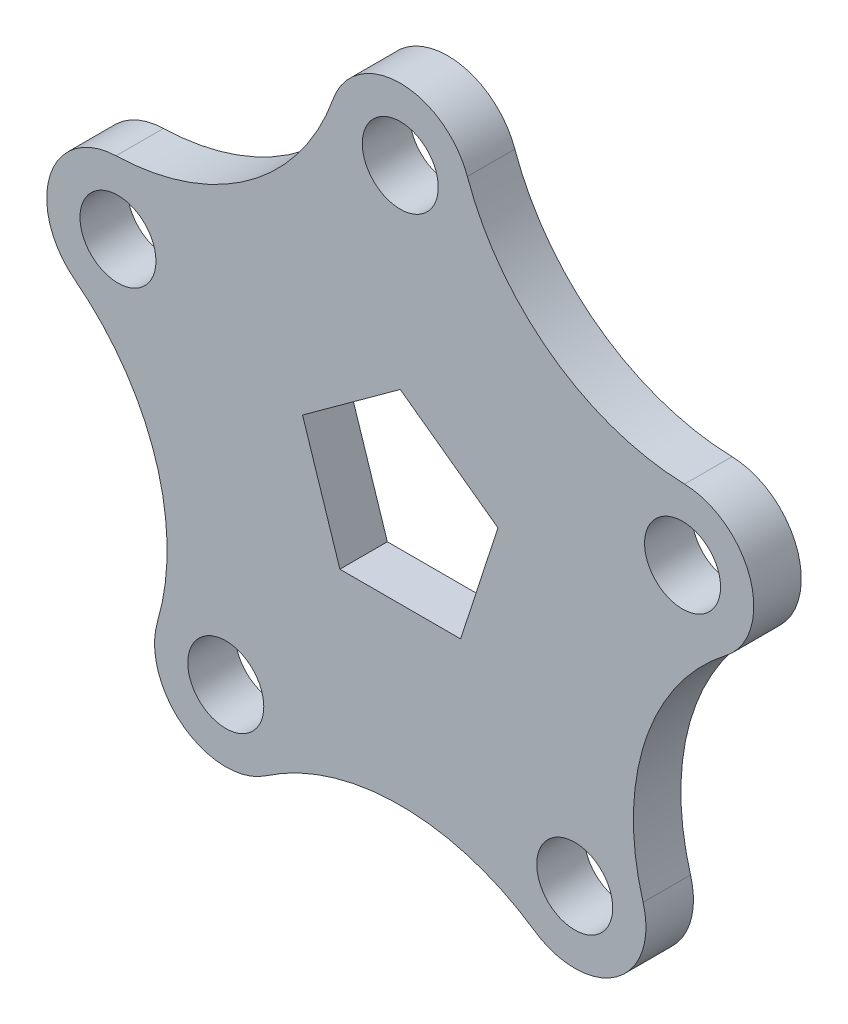
SolidWorks part; units mm, degrees
ref_plane "Płaszczyzna przednia" through (0, 0, 0) normal (0, 0, 1) x (1, 0, 0)
ref_plane "Płaszczyzna górna" through (0, 0, 0) normal (0, 1, 0) x (1, 0, 0)
ref_plane "Płaszczyzna prawa" through (0, 0, 0) normal (1, 0, 0) x (0, 0, -1)
sketch "Szkic1" plane through (0, 0, 0) normal (0, 0, 1) x (1, 0, 0)
  line L0 (0, 21.6312) -> (20.5725, 6.6844)
  line L1 (20.5725, 6.6844) -> (12.7145, -17.5)
  line L2 (12.7145, -17.5) -> (-12.7145, -17.5)
  line L3 (-12.7145, -17.5) -> (-20.5725, 6.6844)
  line L4 (-20.5725, 6.6844) -> (0, 21.6312)
  circle A0 centre (0, 0) radius 17.5
  circle A1 centre (0, 0) radius 62.5
  circle A2 centre (0, 62.5) radius 8
  circle A3 centre (59.441, 19.3136) radius 8
  circle A4 centre (36.7366, -50.5636) radius 8
  circle A5 centre (-36.7366, -50.5636) radius 8
  circle A6 centre (-59.441, 19.3136) radius 8
  arc A7 (-14.1321, 67.5282) -> (14.1321, 67.5282) centre (0, 62.5) cw
  arc A8 (14.1321, 67.5282) -> (59.856, 34.3078) centre (61.2393, 84.2887) ccw
  arc A9 (59.856, 34.3078) -> (68.5902, 7.4269) centre (59.441, 19.3136) cw
  arc A10 (68.5902, 7.4269) -> (51.1252, -46.3248) centre (99.0873, -32.1954) ccw
  arc A11 (51.1252, -46.3248) -> (28.2589, -62.9381) centre (36.7366, -50.5636) cw
  arc A12 (28.2589, -62.9381) -> (-28.2589, -62.9381) centre (0, -104.1865) ccw
  arc A13 (-28.2589, -62.9381) -> (-51.1252, -46.3248) centre (-36.7366, -50.5636) cw
  arc A14 (-51.1252, -46.3248) -> (-68.5902, 7.4269) centre (-99.0873, -32.1954) ccw
  arc A15 (-68.5902, 7.4269) -> (-59.856, 34.3078) centre (-59.441, 19.3136) cw
  arc A16 (-59.856, 34.3078) -> (-14.1321, 67.5282) centre (-61.2393, 84.2887) ccw
  point P22 (0, 0)
  point P23 (0, 0)
  point P26 (0, 0)
  point P48 (0, 0)
  dimension "D1" = 35
  dimension "D2" = 125
  dimension "D3" = 16
  dimension "D5" = 15
  dimension "D6" = 50
  dimension "D4" = 5
  dimension "D7" = 5
extrude "Dodanie-wyciągnięcie1" add sketch "Szkic1" along normal blind 10 contours A16 A1 A6 A14 A5 A12 A4 A10 A3 A8 A2 L3 L4 L0 L1 L2 | A16 A15 A14 A1 A6 | A16 A1 A2 A8 A7 | A10 A9 A8 A1 A3 | A12 A11 A10 A1 A4 | A14 A13 A12 A1 A5
